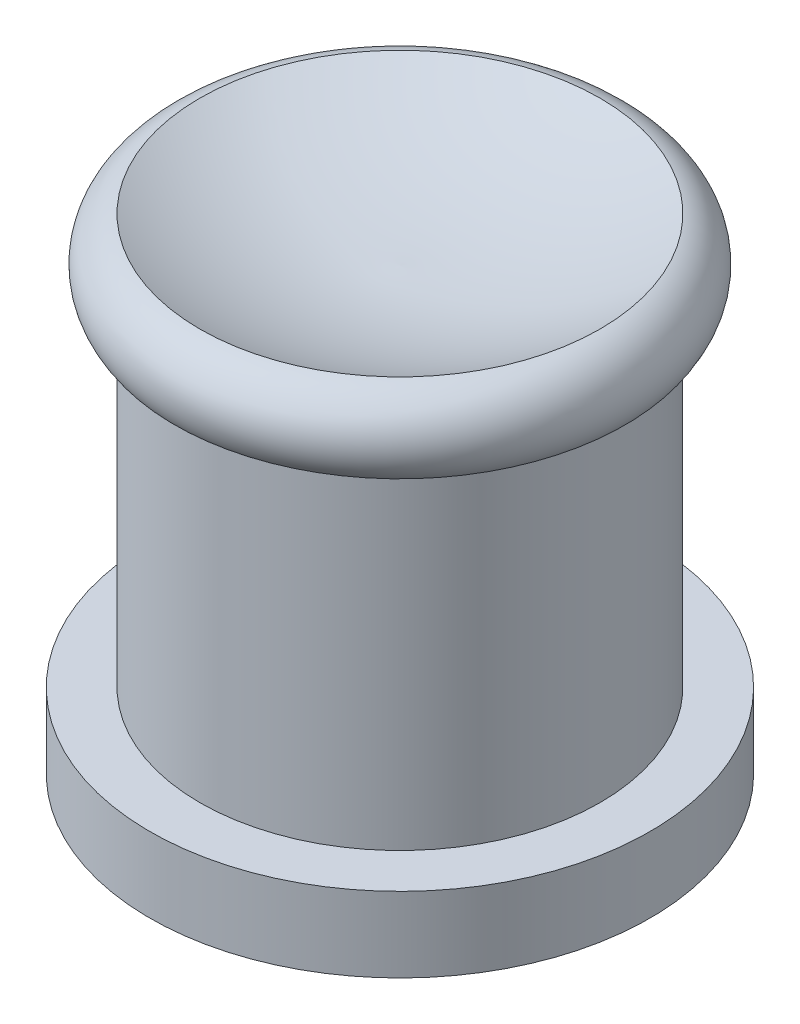
SolidWorks part; units mm, degrees
material "Brass"
ref_plane "Front Plane" through (0, 0, 0) normal (0, 0, 1) x (1, 0, 0)
ref_plane "Top Plane" through (0, 0, 0) normal (0, 1, 0) x (1, 0, 0)
ref_plane "Right Plane" through (0, 0, 0) normal (1, 0, 0) x (0, 0, -1)
sketch "Sketch1" plane through (0, 0, 0) normal (0, 0, 1) x (1, 0, 0)
  line L0 (0, 0.88) -> (0, -0.88) construction
  line L1 (0, 0) -> (0, 0.8)
  line L2 (0, 0.8) -> (0, 0.88)
  line L3 (0, 0) -> (0.5, 0)
  line L4 (0.5, 0) -> (0.5, 0.15)
  line L5 (0.5, 0.15) -> (0.4, 0.15)
  line L6 (0.4, 0.15) -> (0.4, 0.8)
  line L7 (0.4, 0.8) -> (0.45, 0.8289)
  arc A0 (0.45, 0.8289) -> (0.4, 0.97) centre (0.3779, 0.8828) ccw
  arc A1 (0, 0.88) -> (0.4, 0.97) centre (0.0303, 1.6794) ccw
  point P4 (0, 0)
  dimension "D1" = 0.8
  dimension "D6" = 0.4
  dimension "D7" = 0.09
  dimension "D10" = 0.8
  dimension "D2" = 0.08
  dimension "D3" = 0.5
  dimension "D4" = 0.15
  dimension "D5" = 120
  dimension "D8" = 0.17
  dimension "D9" = 0.45
  dimension "D11" = 0.65
revolve "Revolve1" add sketch "Sketch1" angle 360 about L0
